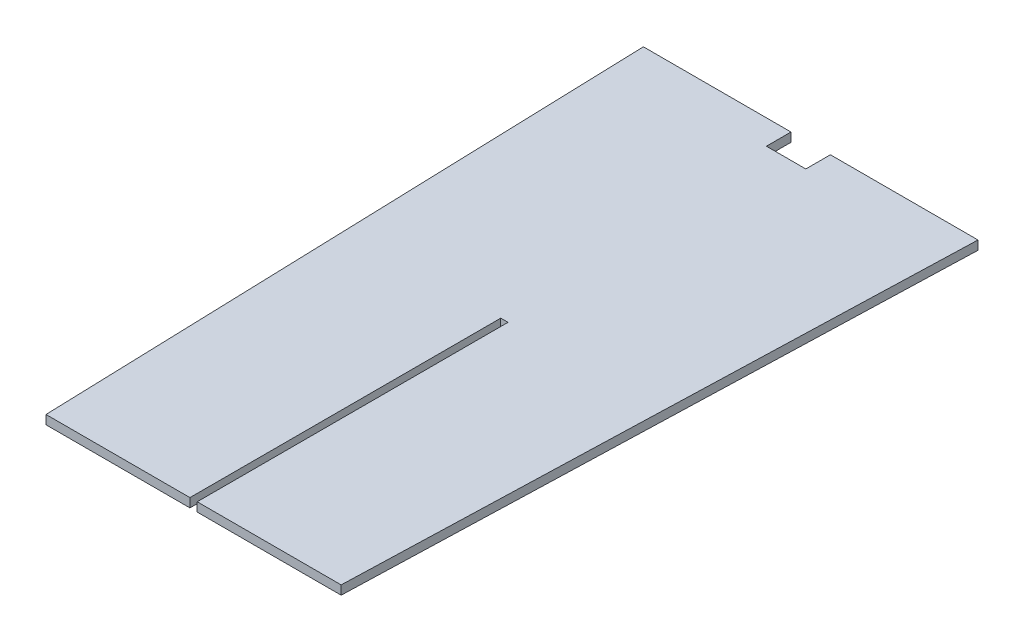
SolidWorks part; units mm, degrees
ref_plane "Front Plane" through (0, 0, 0) normal (0, 0, 1) x (1, 0, 0)
ref_plane "Top Plane" through (0, 0, 0) normal (0, 1, 0) x (1, 0, 0)
ref_plane "Right Plane" through (0, 0, 0) normal (1, 0, 0) x (0, 0, -1)
sketch "Sketch1" plane through (0, 0, 0) normal (0, 1, 0) x (1, 0, 0)
  line L0 (262.6692, 448.3604) -> (367.4633, 448.3604)
  line L1 (276.6773, 10.2104) -> (378.8726, 10.2104)
  line L2 (378.8726, 10.2104) -> (378.8726, 230.8729)
  line L3 (262.6692, 448.3604) -> (276.6773, 10.2104)
  line L4 (500.2354, 448.3604) -> (486.2273, 10.2104)
  line L5 (367.4633, 448.3604) -> (367.4633, 430.8979)
  line L6 (367.4633, 430.8979) -> (395.4414, 430.8979)
  line L7 (395.4414, 448.3604) -> (395.4414, 430.8979)
  line L8 (384.032, 10.2104) -> (384.032, 230.8729)
  line L9 (378.8726, 230.8729) -> (384.032, 230.8729)
  line L10 (384.032, 10.2104) -> (486.2273, 10.2104)
  line L11 (395.4414, 448.3604) -> (500.2354, 448.3604)
extrude "Boss-Extrude1" add sketch "Sketch1" against normal blind 6.35
